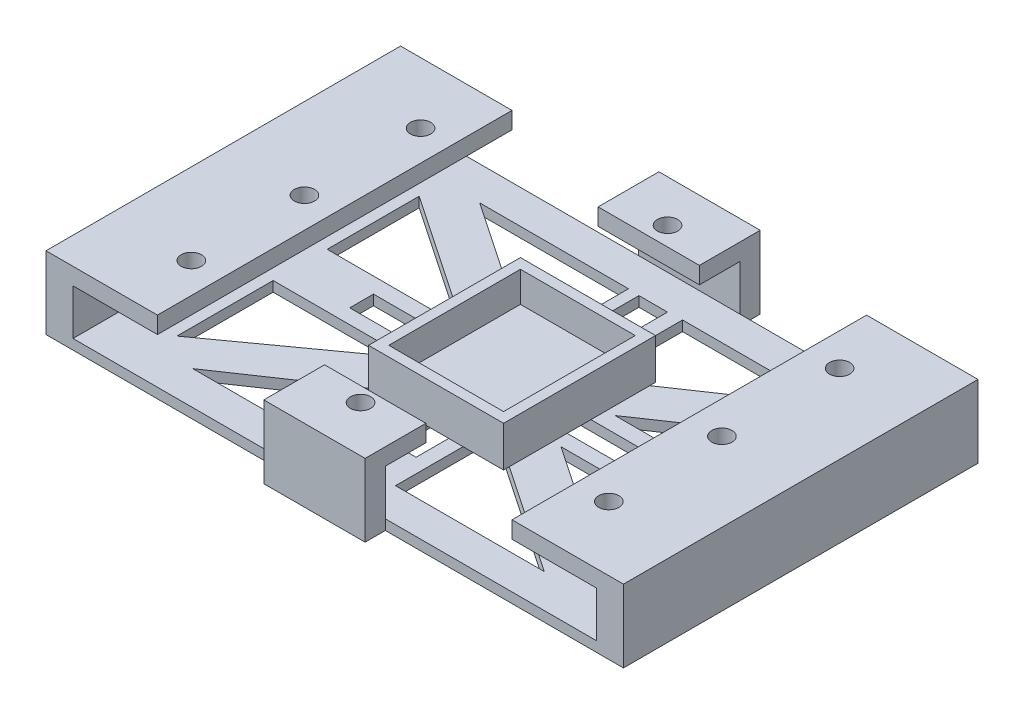
SolidWorks part; units mm, degrees
ref_plane "Front Plane" through (0, 0, 0) normal (0, 0, 1) x (1, 0, 0)
ref_plane "Top Plane" through (0, 0, 0) normal (0, 1, 0) x (1, 0, 0)
ref_plane "Right Plane" through (0, 0, 0) normal (1, 0, 0) x (0, 0, -1)
sketch "Sketch1" plane through (0, 0, 0) normal (0, 1, 0) x (1, 0, 0)
  line L0 (0, 52.5) -> (0, 42.5) construction
  line L1 (-77.5, 52.5) -> (77.5, 52.5)
  line L2 (-77.5, 52.5) -> (-77.5, -52.5)
  line L3 (-77.5, -52.5) -> (77.5, -52.5)
  line L4 (77.5, 52.5) -> (77.5, -52.5)
  line L5 (-77.5, 52.5) -> (-62.7381, 42.5) construction
  line L6 (-77.5, -52.5) -> (-62.7381, -42.5) construction
  line L7 (77.5, 0) -> (62.7381, 0) construction
  line L8 (22.5076, 8) -> (62.7381, 8)
  line L9 (-62.7381, 42.5) -> (62.7381, 42.5)
  line L10 (-62.7381, 42.5) -> (-62.7381, -42.5)
  line L11 (-62.7381, -42.5) -> (62.7381, -42.5)
  line L12 (62.7381, 42.5) -> (62.7381, -42.5)
  line L14 (-29.1943, 12.5297) -> (-22.5076, 8)
  line L15 (-8, 42.5) -> (8, 42.5)
  line L16 (-8, 42.5) -> (-8, 12.6664)
  line L17 (-8, -42.5) -> (8, -42.5)
  line L18 (8, 42.5) -> (8, 12.6664)
  line L19 (21.0615, -21.5146) -> (52.04, -42.5)
  line L20 (21.0615, -21.5146) -> (8, -12.6664)
  line L21 (-62.7381, 8) -> (-22.5076, 8)
  line L22 (-62.7381, 8) -> (-62.7381, -8)
  line L23 (-62.7381, -8) -> (-23.1784, -8)
  line L24 (62.7381, 8) -> (62.7381, -8)
  line L25 (27.7917, -11.5795) -> (62.7381, -35.2529)
  line L26 (27.7917, -11.5795) -> (22.5076, -8)
  line L27 (22.5076, -8) -> (62.7381, -8)
  line L28 (8, -12.6664) -> (8, -42.5)
  line L29 (62.7381, -42.5) -> (77.5, -52.5) construction
  line L30 (-21.0615, -21.5146) -> (-8, -12.6664)
  line L31 (62.7381, 42.5) -> (77.5, 52.5) construction
  line L33 (-8, -12.6664) -> (-8, -42.5)
  line L36 (-29.1943, 12.5297) -> (-62.7381, 35.2529)
  line L37 (0, -42.5) -> (0, -52.5) construction
  line L38 (-22.4641, 22.4647) -> (-8, 12.6664)
  line L39 (-22.4641, 22.4647) -> (-52.04, 42.5)
  line L44 (29.2849, 27.0852) -> (8, 12.6664)
  line L45 (29.2849, 27.0852) -> (52.04, 42.5)
  line L46 (36.015, 17.1502) -> (62.7381, 35.2529)
  line L47 (36.015, 17.1502) -> (22.5076, 8)
  line L48 (-62.7381, 0) -> (-77.5, 0) construction
  line L49 (-21.0615, -21.5146) -> (-52.04, -42.5)
  line L50 (-62.7381, -42.5) -> (-62.7381, -36.5)
  line L51 (-62.7381, -36.5) -> (-23.1784, -8)
  point P0 (0, 0)
  point P10 (0, 0)
  point P15 (0, 0)
  point P20 (0, 0)
  dimension "D1" = 155
  dimension "D2" = 105
  dimension "D3" = 85
  dimension "D4" = 16
  dimension "D5" = 16
  dimension "D8" = 12
  dimension "D9" = 6
extrude "Boss-Extrude1" add sketch "Sketch1" along normal blind 3 contours L51 L10 L11 L49 L30 L33 L28 L20 L19 L12 L25 L26 L27 L8 L47 L46 L9 L45 L44 L18 L16 L38 L39 L36 L14 L21 L23 | L4 L1 L2 L3 L9 L12 L11 L10
sketch "Sketch2" plane through (0, 3, 0) normal (0, 1, 0) x (1, 0, 0)
  line L1 (-77.5, 52.5) -> (-85.5, 52.5)
  line L2 (-77.5, 52.5) -> (-77.5, -52.5)
  line L3 (-77.5, -52.5) -> (-85.5, -52.5)
  line L4 (-85.5, 52.5) -> (-85.5, -52.5)
  line L5 (77.5, 52.5) -> (85.5, 52.5)
  line L6 (77.5, 52.5) -> (77.5, -52.5)
  line L7 (77.5, -52.5) -> (85.5, -52.5)
  line L8 (85.5, 52.5) -> (85.5, -52.5)
  dimension "D1" = 8
  dimension "D2" = 8
extrude "Boss-Extrude2" add sketch "Sketch2" along normal blind 18.5 and the other way through all
sketch "Sketch3" plane through (0, 3, 0) normal (0, 1, 0) x (1, 0, 0)
  line L0 (-77.5, -52.5) -> (77.5, -52.5) construction
  line L1 (-15, -52.5) -> (15, -52.5)
  line L2 (-15, -52.5) -> (-15, -58.5)
  line L3 (-15, -58.5) -> (15, -58.5)
  line L4 (15, -52.5) -> (15, -58.5)
  line L5 (-77.5, 52.5) -> (77.5, 52.5) construction
  line L6 (-15, 52.5) -> (15, 52.5)
  line L7 (-15, 52.5) -> (-15, 58.5)
  line L8 (-15, 58.5) -> (15, 58.5)
  line L9 (15, 52.5) -> (15, 58.5)
  line L10 (0, 0) -> (0, -71.9882) construction
  line L11 (0, -71.9882) -> (0, 71.1301) construction
  dimension "D1" = 30
  dimension "D2" = 30
  dimension "D3" = 6
  dimension "D4" = 6
extrude "Boss-Extrude3" add sketch "Sketch3" along normal blind 18.5 and the other way through all
sketch "Sketch4" plane through (0, 21.5, 0) normal (0, 1, 0) x (1, 0, 0)
  line L0 (-77.5, -52.5) -> (-15, -52.5) construction
  line L1 (-77.5, 52.5) -> (-52.5, 52.5)
  line L2 (-77.5, 52.5) -> (-77.5, -52.5)
  line L3 (-77.5, -52.5) -> (-52.5, -52.5)
  line L4 (-52.5, 52.5) -> (-52.5, -52.5)
  line L5 (15, -52.5) -> (77.5, -52.5) construction
  line L6 (77.5, 52.5) -> (52.5, 52.5)
  line L7 (77.5, 52.5) -> (77.5, -52.5)
  line L8 (77.5, -52.5) -> (52.5, -52.5)
  line L9 (52.5, 52.5) -> (52.5, -52.5)
  line L11 (-15, 52.5) -> (15, 52.5)
  line L12 (-15, 52.5) -> (-15, 40.5)
  line L13 (-15, 40.5) -> (15, 40.5)
  line L14 (15, 52.5) -> (15, 40.5)
  line L15 (-15, -52.5) -> (15, -52.5)
  line L16 (-15, -52.5) -> (-15, -40.5)
  line L17 (-15, -40.5) -> (15, -40.5)
  line L18 (15, -52.5) -> (15, -40.5)
  dimension "D1" = 25
  dimension "D2" = 25
  dimension "D3" = 12
  dimension "D4" = 12
extrude "Boss-Extrude4" add sketch "Sketch4" against normal blind 5
sketch "Sketch5" plane through (0, 3, 0) normal (0, 1, 0) x (1, 0, 0)
  line L1 (-4.6939, 42.2958) -> (3.7587, 42.2958)
  line L2 (-4.6939, 42.2958) -> (-4.6939, -32.1647)
  line L3 (-4.6939, -32.1647) -> (3.7587, -32.1647)
  line L4 (3.7587, 42.2958) -> (3.7587, -32.1647)
  line L5 (-44.3911, -3.6677) -> (46.4012, -3.6677)
  line L6 (-44.3911, -3.6677) -> (-44.3911, 3.3735)
  line L7 (-44.3911, 3.3735) -> (46.4012, 3.3735)
  line L8 (46.4012, -3.6677) -> (46.4012, 3.3735)
  line L13 (-81.6748, 42.2958) -> (-71.3232, 42.2958)
  line L14 (-81.6748, 42.2958) -> (-81.6748, -32.1647)
  line L15 (-81.6748, -32.1647) -> (-71.3232, -32.1647)
  line L16 (-71.3232, 42.2958) -> (-71.3232, -32.1647)
  line L17 (68.2638, 42.2958) -> (77.9423, 42.2958)
  line L18 (68.2638, 42.2958) -> (68.2638, -32.1647)
  line L19 (68.2638, -32.1647) -> (77.9423, -32.1647)
  line L20 (77.9423, 42.2958) -> (77.9423, -32.1647)
  circle A0 centre (0, 0) radius 12
extrude "Cut-Extrude1" cut sketch "Sketch5" against normal blind 5 contours A0 L4 L1 L2 | L7 A0 L4 | L4 A0 L2 L7 | L2 A0 L7 | L7 A0 L5 L2 | L7 L2 L5 L4 | L5 A0 L7 L4 | L4 A0 L5 | L2 A0 L4 L5 | A0 L2 L3 L4 | L5 A0 L2
sketch "Sketch7" plane through (0, 21.5, 0) normal (0, 1, 0) x (1, 0, 0)
  line L0 (-22.5076, 8) -> (-62.7381, 35.2529) construction
  line L1 (62.7381, 35.2529) -> (22.5076, 8) construction
  circle A0 centre (-61.4718, 0) radius 3
  circle A1 centre (62.1606, 0) radius 3
  circle A2 centre (-61.4718, 34.3951) radius 3
  circle A3 centre (-61.4718, -33.491) radius 3
  circle A4 centre (62.1606, 34.8617) radius 3
  circle A5 centre (62.1606, -33.491) radius 3
  circle A6 centre (0, -44.8555) radius 3
  circle A7 centre (0, 46.0608) radius 3
extrude "Cut-Extrude3" cut sketch "Sketch7" against normal blind 5
sketch "Sketch8" plane through (0, 3, 0) normal (0, 1, 0) x (1, 0, 0)
  line L1 (-20, 22.5) -> (20, 22.5)
  line L2 (-20, 22.5) -> (-20, -22.5)
  line L3 (-20, -22.5) -> (20, -22.5)
  line L4 (20, 22.5) -> (20, -22.5)
  line L5 (-20, 22.5) -> (20, -22.5) construction
  line L6 (-20, -22.5) -> (20, 22.5) construction
  point P0 (0, 0)
  dimension "D1" = 40
  dimension "D2" = 45
extrude "Boss-Extrude7" add sketch "Sketch8" along normal blind 12
sketch "Sketch10" plane through (0, 15, 0) normal (0, 1, 0) x (1, 0, 0)
  line L1 (-17, 19.5) -> (17, 19.5)
  line L2 (-17, 19.5) -> (-17, -19.5)
  line L3 (-17, -19.5) -> (17, -19.5)
  line L4 (17, 19.5) -> (17, -19.5)
  line L5 (-17, 19.5) -> (17, -19.5) construction
  line L6 (-17, -19.5) -> (17, 19.5) construction
  point P0 (0, 0)
  dimension "D1" = 34
  dimension "D2" = 39
extrude "Cut-Extrude4" cut sketch "Sketch10" against normal blind 9 contours L2 L1 L4 L3
